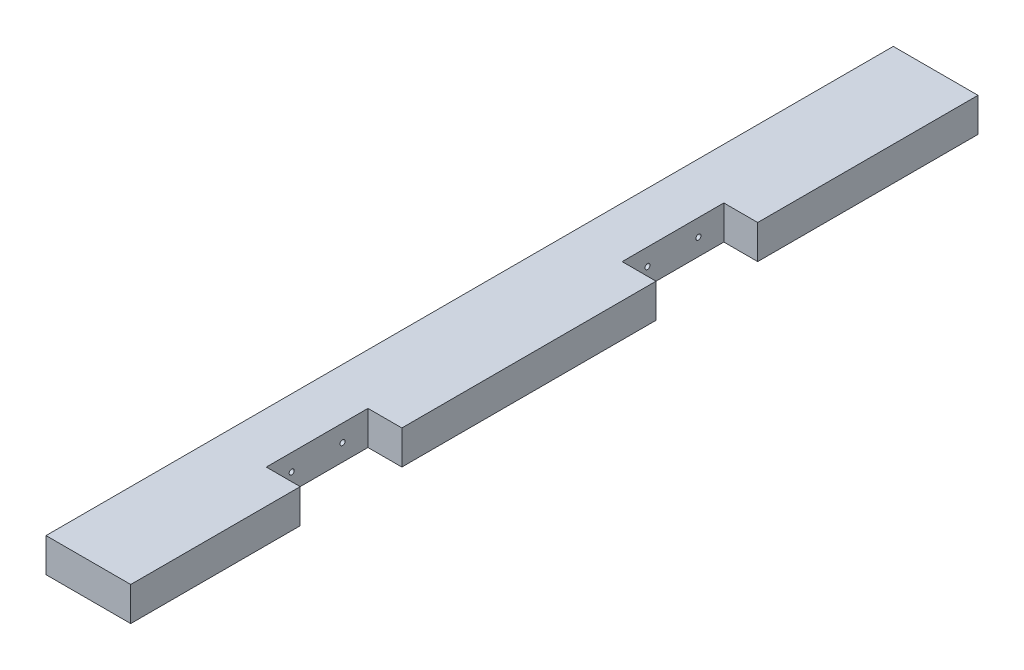
SolidWorks part; units mm, degrees
material "Kiefer"
ref_plane "Ebene vorne" through (0, 0, 0) normal (0, 0, 1) x (1, 0, 0)
ref_plane "Ebene oben" through (0, 0, 0) normal (0, 1, 0) x (1, 0, 0)
ref_plane "Ebene rechts" through (0, 0, 0) normal (1, 0, 0) x (0, 0, -1)
sketch "Skizze1" plane through (0, 0, 0) normal (0, 0, 1) x (1, 0, 0)
  line L1 (-25, 10) -> (25, 10)
  line L2 (-25, 10) -> (-25, -10)
  line L3 (-25, -10) -> (25, -10)
  line L4 (25, 10) -> (25, -10)
  line L5 (-25, 10) -> (25, -10) construction
  line L6 (-25, -10) -> (25, 10) construction
  point P0 (0, 0)
  dimension "D1" = 50
  dimension "D2" = 20
extrude "Aufsatz-Linear austragen1" add sketch "Skizze1" along normal blind 500
sketch "Skizze2" plane through (0, 10, 0) normal (0, 1, 0) x (1, 0, 0)
  line L0 (25, -500) -> (25, 0) construction
  line L1 (25, -340) -> (5, -340)
  line L2 (25, -340) -> (25, -400)
  line L3 (25, -400) -> (5, -400)
  line L4 (5, -340) -> (5, -400)
  line L6 (25, -500) -> (-25, -500) construction
  line L7 (25, -130) -> (5, -130)
  line L8 (25, -130) -> (25, -190)
  line L9 (25, -190) -> (5, -190)
  line L10 (5, -130) -> (5, -190)
  dimension "D1" = 60
  dimension "D2" = 20
  dimension "D3" = 100
  dimension "D4" = 150
extrude "Schnitt-Linear austragen1" cut sketch "Skizze2" against normal through all
sketch "Skizze3" plane through (5, 0, 0) normal (1, 0, 0) x (0, 0, -1)
  line L0 (-340, -10) -> (-400, -10) construction
  line L1 (-400, 10) -> (-370, 10) construction
  line L2 (-400, 10) -> (-400, -10) construction
  line L3 (-400, -10) -> (-370, -10) construction
  line L4 (-370, 10) -> (-370, -10) construction
  line L5 (-400, 10) -> (-370, -10) construction
  line L6 (-400, -10) -> (-370, 10) construction
  line L7 (-130, -10) -> (-190, -10) construction
  line L8 (-370, -10) -> (-340, -10) construction
  line L9 (-370, -10) -> (-370, 10) construction
  line L10 (-370, 10) -> (-340, 10) construction
  line L11 (-340, -10) -> (-340, 10) construction
  line L12 (-370, -10) -> (-340, 10) construction
  line L13 (-370, 10) -> (-340, -10) construction
  line L14 (-190, 10) -> (-160, 10) construction
  line L15 (-190, 10) -> (-190, -10) construction
  line L16 (-190, -10) -> (-160, -10) construction
  line L17 (-160, 10) -> (-160, -10) construction
  line L18 (-190, 10) -> (-160, -10) construction
  line L19 (-190, -10) -> (-160, 10) construction
  line L21 (-160, -10) -> (-130, -10) construction
  line L22 (-160, -10) -> (-160, 10) construction
  line L23 (-160, 10) -> (-130, 10) construction
  line L24 (-130, -10) -> (-130, 10) construction
  line L25 (-160, -10) -> (-130, 10) construction
  line L26 (-160, 10) -> (-130, -10) construction
  circle A0 centre (-385, 0) radius 1.5
  circle A1 centre (-355, 0) radius 1.5
  circle A2 centre (-175, 0) radius 1.5
  circle A3 centre (-145, 0) radius 1.5
  point P4 (-385, 0)
  point P10 (-355, 0)
  point P20 (-175, 0)
  point P26 (-145, 0)
  dimension "D1" = 3
extrude "Schnitt-Linear austragen2" cut sketch "Skizze3" against normal blind 20
